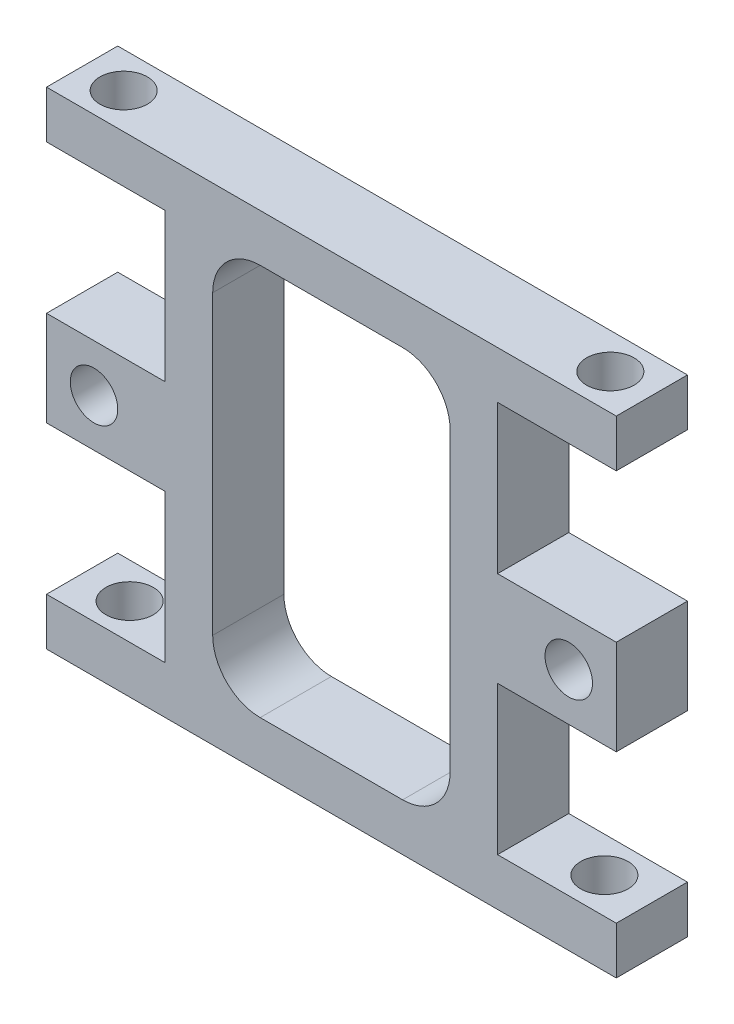
SolidWorks part; units mm, degrees
material "6061-T6 (SS)"
ref_plane "Front" through (0, 0, 0) normal (0, 0, 1) x (1, 0, 0)
ref_plane "Top" through (0, 0, 0) normal (0, 1, 0) x (1, 0, 0)
ref_plane "Right" through (0, 0, 0) normal (1, 0, 0) x (0, 0, -1)
sketch "Sketch2" plane through (0, 0, 0) normal (0, 0, 1) x (1, 0, 0)
  line L0 (-15.875, 26.1938) -> (15.875, -26.1937) construction
  line L1 (-15.875, -26.1938) -> (15.875, 26.1938) construction
  line L2 (-22.225, -26.1937) -> (-22.225, -6.35)
  line L3 (-38.1, 32.5438) -> (38.1, 32.5438)
  line L4 (22.225, -26.1937) -> (22.225, -6.35)
  line L5 (-15.875, -26.1937) -> (15.875, -26.1937)
  line L6 (-22.225, 6.35) -> (-22.225, 26.1938)
  line L7 (-15.875, 26.1938) -> (15.875, 26.1938)
  line L8 (-15.875, 26.1938) -> (-15.875, -26.1937)
  line L9 (22.225, 6.35) -> (38.1, 6.35)
  line L10 (15.875, 26.1938) -> (15.875, -26.1937)
  line L11 (22.225, -26.1937) -> (38.1, -26.1937)
  line L13 (-38.1, -32.5437) -> (38.1, -32.5437)
  line L14 (38.1, -26.1937) -> (38.1, -32.5437)
  line L15 (-22.225, -26.1937) -> (-38.1, -26.1937)
  line L16 (22.225, -6.35) -> (38.1, -6.35)
  line L17 (38.1, 6.35) -> (38.1, -6.35)
  line L18 (-38.1, -26.1937) -> (-38.1, -32.5437)
  line L19 (-22.225, 6.35) -> (-38.1, 6.35)
  line L20 (22.225, 6.35) -> (22.225, 26.1938)
  line L21 (22.225, 26.1938) -> (38.1, 26.1938)
  line L22 (38.1, 32.5438) -> (38.1, 26.1938)
  line L23 (-22.225, -6.35) -> (-38.1, -6.35)
  line L24 (-38.1, 6.35) -> (-38.1, -6.35)
  line L25 (-22.225, 26.1938) -> (-38.1, 26.1938)
  line L26 (-38.1, 32.5438) -> (-38.1, 26.1938)
  circle A0 centre (-31.75, 0) radius 3.175
  circle A1 centre (31.75, 0) radius 3.175
  point P0 (0, 0)
  point P3 (0, 0)
  point P4 (0, 0)
  point P29 (38.1, 0)
  point P30 (-38.1, 0)
  dimension "D16" = 6.35
  dimension "D17" = 6.35
  dimension "D18" = 6.35
  dimension "D19" = 6.35
  dimension "D1" = 31.75
  dimension "D2" = 6.35
  dimension "D3" = 6.35
  dimension "D4" = 52.3875
  dimension "D5" = 6.35
  dimension "D6" = 15.875
  dimension "D7" = 15.875
  dimension "D8" = 15.875
  dimension "D9" = 6.35
  dimension "D10" = 6.35
  dimension "D11" = 15.875
  dimension "D12" = 15.875
  dimension "D13" = 15.875
  dimension "D14" = 12.7
  dimension "D15" = 12.7
extrude "Boss-Extrude1" add sketch "Sketch2" along normal blind 9.525
fillet "Fillet1" radius 6.35 4 edges at (15.875, 26.1938, 4.7625) (-15.875, 26.1938, 4.7625) (15.875, -26.1937, 4.7625) (-15.875, -26.1937, 4.7625)
sketch "Sketch3" plane through (0, 32.5438, 0) normal (0, 1, 0) x (1, 0, 0)
  line L0 (38.1, 0) -> (-38.1, 0) construction
  line L1 (-38.1, -9.525) -> (-38.1, 0) construction
  line L2 (38.1, -9.525) -> (38.1, 0) construction
  circle A0 centre (-32.5438, -4.7625) radius 3.175
  circle A1 centre (32.5438, -4.7625) radius 3.175
  dimension "D1" = 6.35
  dimension "D2" = 6.35
  dimension "D3" = 4.7625
  dimension "D4" = 4.7625
  dimension "D5" = 5.5562
  dimension "D6" = 5.5562
extrude "Cut-Extrude1" cut sketch "Sketch3" against normal up to next
sketch "Sketch4" plane through (0, -32.5437, 0) normal (0, -1, 0) x (1, 0, 0)
  line L0 (-38.1, 9.525) -> (-38.1, 0) construction
  line L1 (38.1, 9.525) -> (38.1, 0) construction
  line L2 (-38.1, 9.525) -> (38.1, 9.525) construction
  circle A0 centre (-31.75, 4.7625) radius 3.175
  circle A1 centre (31.75, 4.7625) radius 3.175
  dimension "D1" = 6.35
  dimension "D2" = 6.35
  dimension "D3" = 6.35
  dimension "D4" = 6.35
  dimension "D5" = 4.7625
  dimension "D6" = 4.7625
extrude "Cut-Extrude2" cut sketch "Sketch4" against normal up to next
